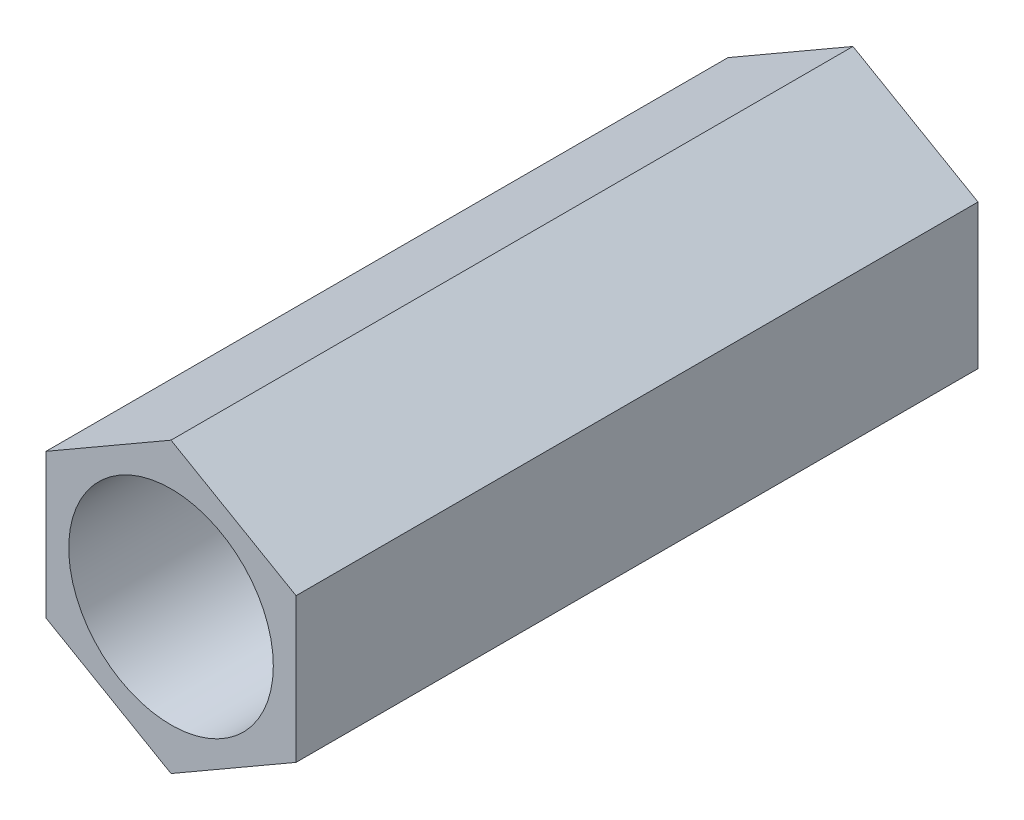
SolidWorks part; units mm, degrees
material "Brass"
ref_plane "Front Plane" through (0, 0, 0) normal (0, 0, 1) x (1, 0, 0)
ref_plane "Top Plane" through (0, 0, 0) normal (0, 1, 0) x (1, 0, 0)
ref_plane "Right Plane" through (0, 0, 0) normal (1, 0, 0) x (0, 0, -1)
sketch "Sketch1" plane through (0, 0, 0) normal (0, 0, 1) x (1, 0, 0)
  line L1 (0, 3.1754) -> (-2.75, 1.5877)
  line L2 (-2.75, 1.5877) -> (-2.75, -1.5877)
  line L3 (-2.75, -1.5877) -> (0, -3.1754)
  line L4 (0, -3.1754) -> (2.75, -1.5877)
  line L5 (2.75, -1.5877) -> (2.75, 1.5877)
  line L6 (2.75, 1.5877) -> (0, 3.1754)
  circle A0 centre (0, 0) radius 2.75 construction
  circle A1 centre (0, 0) radius 2.25
  dimension "D2" = 4.5
  dimension "D1" = 5.5
extrude "Boss-Extrude1" add sketch "Sketch1" along normal blind 15
